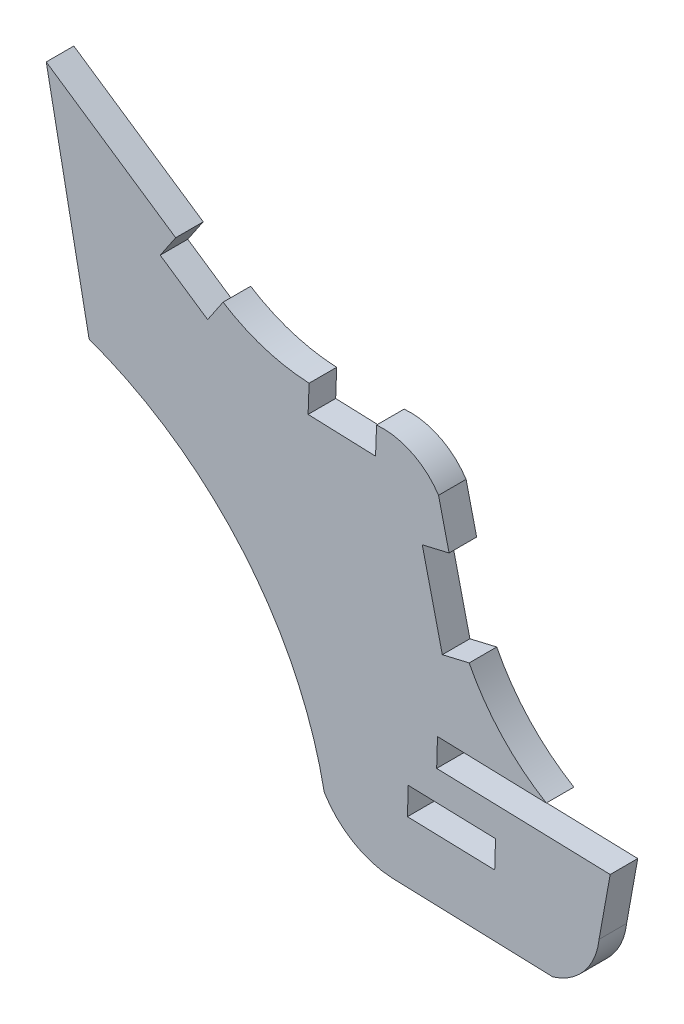
SolidWorks part; units mm, degrees
ref_plane "Front" through (0, 0, 0) normal (0, 0, 1) x (1, 0, 0)
ref_plane "Top" through (0, 0, 0) normal (0, 1, 0) x (1, 0, 0)
ref_plane "Right" through (0, 0, 0) normal (1, 0, 0) x (0, 0, -1)
sketch "Sketch1" plane through (0, 0, 0) normal (0, 0, 1) x (1, 0, 0)
  line L0 (468.4851, 336.7662) -> (485.9877, 336.1881)
  line L1 (470.1758, 343.3822) -> (479.6717, 343.1039)
  line L2 (479.7596, 346.1026) -> (470.2636, 346.3809)
  line L3 (492.2381, 348.9659) -> (473.3557, 349.5197)
  line L4 (473.4452, 352.5698) -> (485.2862, 352.2225)
  line L5 (470.2636, 346.3809) -> (470.1758, 343.3822)
  line L6 (473.3557, 349.5197) -> (473.4452, 352.5698)
  line L7 (479.6717, 343.1039) -> (479.7596, 346.1026)
  line L8 (491.0265, 342.2414) -> (492.2381, 348.9659)
  line L9 (431.6888, 390.6809) -> (435.5324, 371.0679)
  line L10 (444.9536, 385.329) -> (433.3699, 393.1657)
  line L11 (443.2726, 382.8442) -> (444.9536, 385.329)
  line L12 (448.4326, 379.3533) -> (443.2726, 382.8442)
  line L13 (448.4326, 379.3533) -> (450.1137, 381.838)
  line L14 (433.3699, 393.1657) -> (430.8705, 394.8566)
  line L15 (431.6888, 390.6809) -> (430.8705, 394.8566)
  line L16 (474.7056, 370.4964) -> (473.5602, 375.3629)
  line L17 (471.7909, 369.8104) -> (474.7056, 370.4964)
  line L18 (473.972, 360.5436) -> (476.8922, 361.2309)
  line L19 (471.7909, 369.8104) -> (473.972, 360.5436)
  line L20 (466.7892, 377.9068) -> (466.7048, 375.6154)
  line L21 (459.3648, 375.8858) -> (459.4752, 378.8837)
  line L22 (466.7048, 375.6154) -> (459.3648, 375.8858)
  line L23 (466.7892, 377.9068) -> (466.8152, 378.6134)
  arc A0 (461.1265, 341.1423) -> (435.5324, 371.0679) centre (421.8684, 333.4741) ccw
  arc A1 (476.8922, 361.2309) -> (485.2862, 352.2225) centre (496.7479, 371.3173) ccw
  arc A2 (461.1265, 341.1423) -> (468.4851, 336.7662) centre (468.9679, 345.953) ccw
  arc A3 (485.9877, 336.1881) -> (491.0265, 342.2414) centre (483.9262, 343.0279) ccw
  arc A4 (450.1137, 381.838) -> (459.4752, 378.8837) centre (460.3235, 397.8812) ccw
  arc A5 (473.5602, 375.3629) -> (466.8152, 378.6134) centre (467.4777, 371.3648) ccw
  dimension "D1" = 6.23
  dimension "D2" = 7.34
  dimension "D3" = 9.52
extrude "Base-Extrude" add sketch "Sketch1" along normal blind 3
